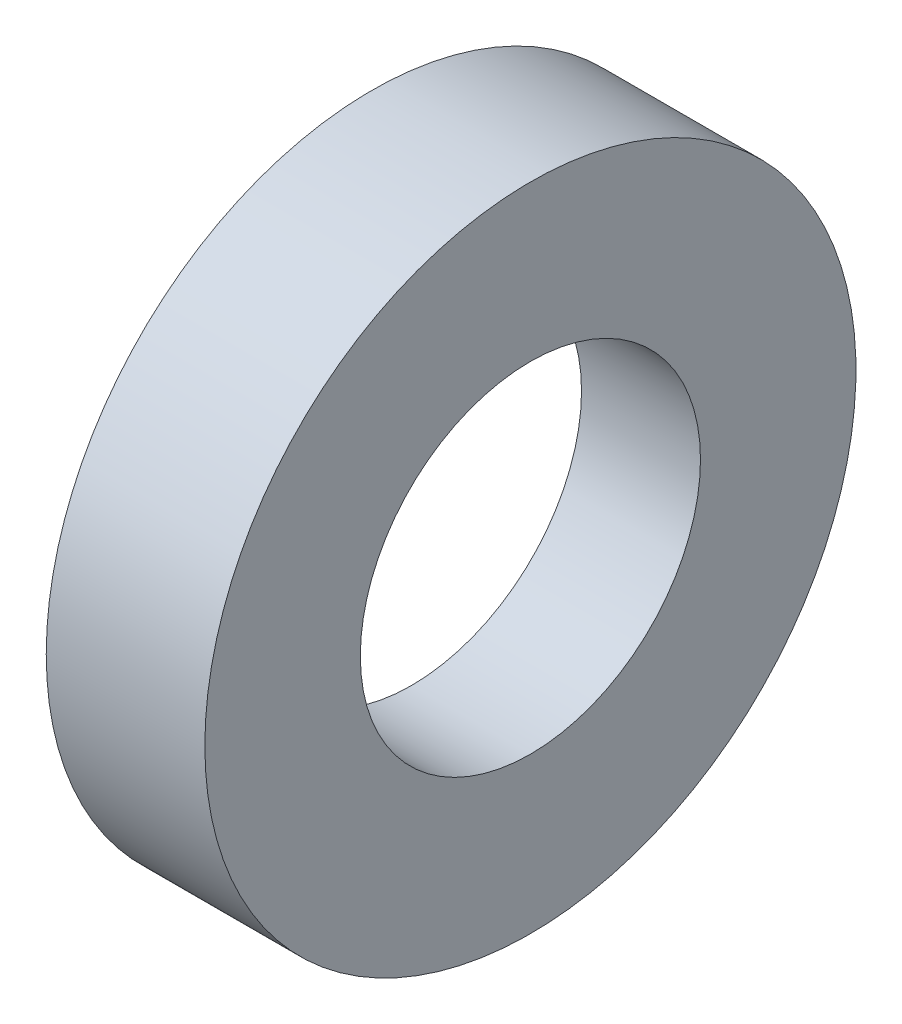
SolidWorks part; units mm, degrees
ref_plane "Front Plane" through (0, 0, 0) normal (0, 0, 1) x (1, 0, 0)
ref_plane "Top Plane" through (0, 0, 0) normal (0, 1, 0) x (1, 0, 0)
ref_plane "Right Plane" through (0, 0, 0) normal (1, 0, 0) x (0, 0, -1)
sketch "Sketch1" plane through (0, 0, 0) normal (0, 0, 1) x (1, 0, 0)
  line L0 (-5.6784, 16.3) -> (5.7216, 16.3)
  line L1 (5.7216, 16.3) -> (5.7216, 31.2)
  line L2 (5.7216, 31.2) -> (-9.4784, 31.2)
  line L3 (-9.4784, 31.2) -> (-9.4784, 22.3)
  line L4 (-9.4784, 22.3) -> (-5.6784, 22.3)
  line L5 (-5.6784, 22.3) -> (-5.6784, 16.3)
  line L6 (0, 0) -> (7.2765, 0) construction
  dimension "D1" = 16.3
  dimension "D2" = 14.9
  dimension "D3" = 8.9
  dimension "D4" = 11.4
  dimension "D5" = 15.2
revolve "Revolve1" add sketch "Sketch1" angle 360 about L6
